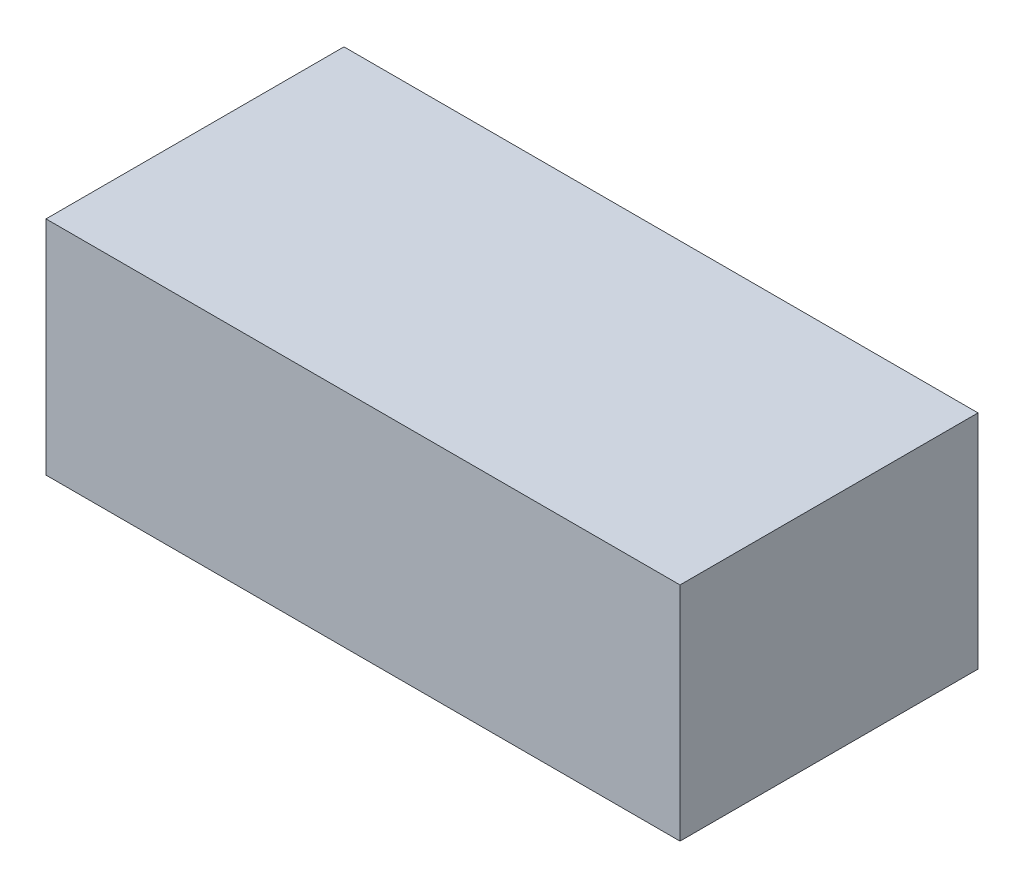
SolidWorks part; units mm, degrees
ref_plane "Plan de face" through (0, 0, 0) normal (0, 0, 1) x (1, 0, 0)
ref_plane "Plan de dessus" through (0, 0, 0) normal (0, 1, 0) x (1, 0, 0)
ref_plane "Plan de droite" through (0, 0, 0) normal (1, 0, 0) x (0, 0, -1)
sketch "Esquisse1" plane through (0, 0, 0) normal (0, 0, 1) x (1, 0, 0)
  line L1 (-35, 25.3704) -> (65, 25.3704)
  line L2 (-35, 25.3704) -> (-35, -9.6296)
  line L3 (-35, -9.6296) -> (65, -9.6296)
  line L4 (65, 25.3704) -> (65, -9.6296)
  dimension "D1" = 100
  dimension "D2" = 35
extrude "Boss.-Extru.1" add sketch "Esquisse1" along normal blind 47
